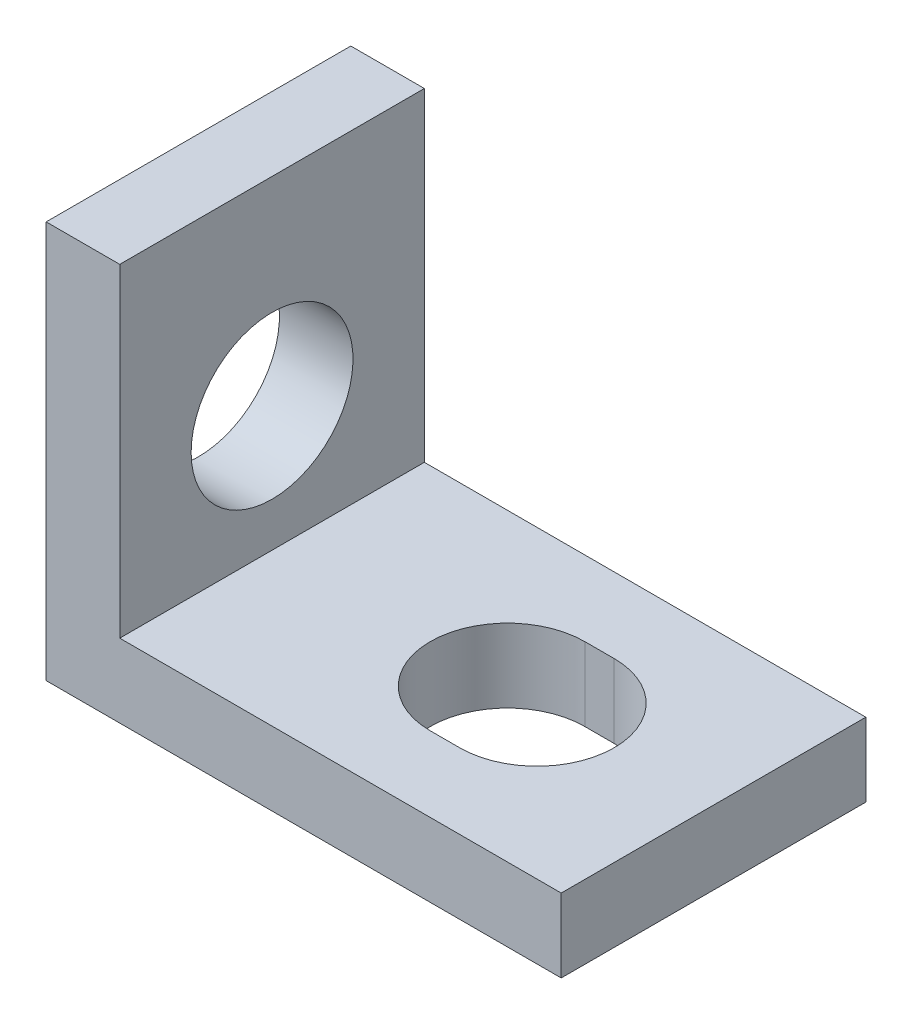
SolidWorks part; units mm, degrees
ref_plane "前视基准面" through (0, 0, 0) normal (0, 0, 1) x (1, 0, 0)
ref_plane "上视基准面" through (0, 0, 0) normal (0, 1, 0) x (1, 0, 0)
ref_plane "右视基准面" through (0, 0, 0) normal (1, 0, 0) x (0, 0, -1)
sketch "草图1" plane through (0, 0, 0) normal (0, 0, 1) x (1, 0, 0)
  line L0 (0, 0) -> (0, 5.4)
  line L1 (0, 5.4) -> (1, 5.4)
  line L2 (1, 5.4) -> (1, 1)
  line L3 (1, 1) -> (7, 1)
  line L4 (7, 1) -> (7, 0)
  line L5 (7, 0) -> (0, 0)
  dimension "D1" = 1
  dimension "D2" = 1
  dimension "D3" = 7
  dimension "D4" = 5.4
extrude "凸台-拉伸1" add sketch "草图1" along normal blind 4.14
sketch "草图3" plane through (0, 0, 0) normal (-1, 0, 0) x (0, 0, 1)
  line L0 (4.14, 0) -> (0, 0) construction
  line L1 (0, 5.4) -> (0, 0) construction
  circle A0 centre (2.07, 2.7) radius 1.1
  dimension "D1" = 2.7
  dimension "D2" = 2.07
extrude "切除-拉伸1" cut sketch "草图3" against normal through all
sketch "草图4" plane through (0, 0, 0) normal (0, -1, 0) x (1, 0, 0)
  line L0 (4.6, 2.07) -> (4.2, 2.07) construction
  line L1 (4.6, 1.02) -> (4.2, 1.02)
  line L2 (4.6, 3.12) -> (4.2, 3.12)
  line L4 (0, 0) -> (7, 0) construction
  line L5 (7, 4.14) -> (7, 0) construction
  arc A0 (4.6, 1.02) -> (4.6, 3.12) centre (4.6, 2.07) ccw
  arc A1 (4.2, 3.12) -> (4.2, 1.02) centre (4.2, 2.07) ccw
  point P2 (4.4, 2.07)
  point P7 (0, 0)
  point P13 (7, 0.775)
  dimension "D1" = 2.6
  dimension "D2" = 2.07
extrude "切除-拉伸2" cut sketch "草图4" against normal through all
